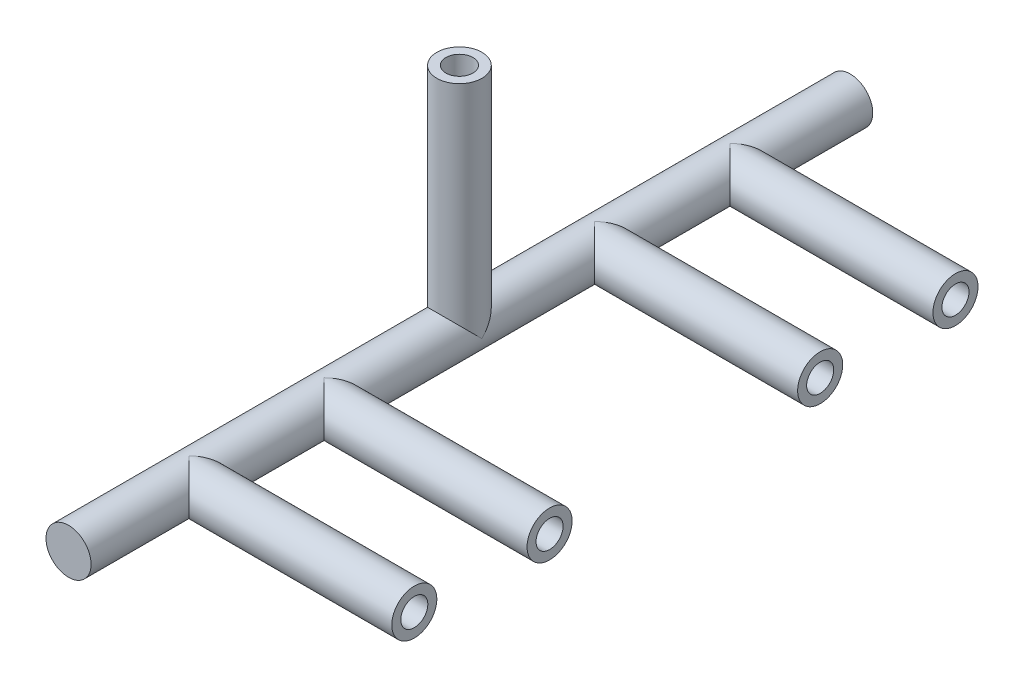
SolidWorks part; units mm, degrees
ref_plane "前视基准面" through (0, 0, 0) normal (0, 0, 1) x (1, 0, 0)
ref_plane "上视基准面" through (0, 0, 0) normal (0, 1, 0) x (1, 0, 0)
ref_plane "右视基准面" through (0, 0, 0) normal (1, 0, 0) x (0, 0, -1)
sketch "草图1" plane through (0, 0, 0) normal (0, 0, 1) x (1, 0, 0)
  circle A0 centre (0, 0) radius 7.5
  circle A1 centre (0, 0) radius 4.5
  dimension "D1" = 15
  dimension "D2" = 9
extrude "凸台-拉伸1" add sketch "草图1" along normal mid plane 250
ref_plane "基准面1" through (0, 75, 0) normal (0, 1, 0) x (1, 0, 0)
sketch "草图2" plane through (0, 75, 0) normal (0, 1, 0) x (1, 0, 0)
  circle A0 centre (0, 0) radius 7.5
  circle A1 centre (0, 0) radius 4.5
  dimension "D1" = 9
  dimension "D2" = 15
extrude "凸台-拉伸2" add sketch "草图2" against normal up to surface (67.5 mm away)
ref_plane "基准面2" through (75, 0, 0) normal (1, 0, 0) x (0, 0, -1)
sketch "草图3" plane through (75, 0, 0) normal (1, 0, 0) x (0, 0, -1)
  line L0 (0, 0) -> (0, -98.0601) construction
  circle A0 centre (-45, 0) radius 4.5
  circle A1 centre (-45, 0) radius 7.5
  circle A2 centre (-90, 0) radius 4.5
  circle A3 centre (-90, 0) radius 7.5
  circle A4 centre (90, 0) radius 7.5
  circle A5 centre (90, 0) radius 4.5
  circle A6 centre (45, 0) radius 7.5
  circle A7 centre (45, 0) radius 4.5
  dimension "D1" = 9
  dimension "D2" = 15
  dimension "D3" = 9
  dimension "D4" = 15
  dimension "D5" = 45
  dimension "D6" = 45
extrude "凸台-拉伸3" add sketch "草图3" against normal up to surface (67.5 mm away)
sketch "草图4" plane through (0, 0, -125) normal (0, 0, -1) x (-1, 0, 0)
  circle A0 centre (0, 0) radius 7.5
  dimension "D1" = 15
sketch "草图5" plane through (0, 0, 125) normal (0, 0, 1) x (1, 0, 0)
  circle A0 centre (0, 0) radius 7.5
  dimension "D1" = 15
extrude "凸台-拉伸4" add sketch "草图4" along normal blind 5
extrude "凸台-拉伸5" add sketch "草图5" along normal blind 5
